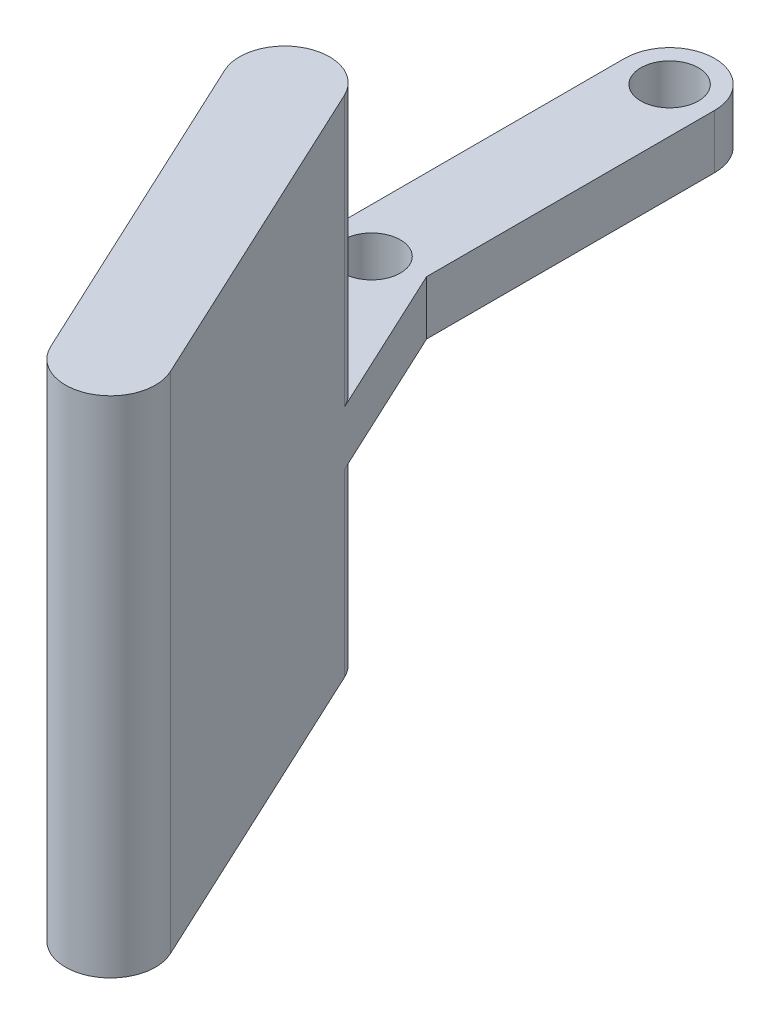
SolidWorks part; units mm, degrees
ref_plane "Front Plane" through (0, 0, 0) normal (0, 0, 1) x (1, 0, 0)
ref_plane "Top Plane" through (0, 0, 0) normal (0, 1, 0) x (1, 0, 0)
ref_plane "Right Plane" through (0, 0, 0) normal (1, 0, 0) x (0, 0, -1)
sketch "Sketch1" plane through (0, 0, 0) normal (0, 1, 0) x (1, 0, 0)
  line L0 (0, 0) -> (0, -16.5529) construction
  line L1 (2.5, 0) -> (2.5, -16.5529)
  line L2 (-2.5, 0) -> (-2.5, -16.5529)
  arc A0 (2.5, 0) -> (-2.5, 0) centre (0, 0) ccw
  arc A1 (-2.5, -16.5529) -> (2.5, -16.5529) centre (0, -16.5529) ccw
  point P3 (0, -8.2765)
  dimension "D1" = 2.5
  dimension "D2" = 16.5529
extrude "Boss-Extrude1" add sketch "Sketch1" along normal blind 3
sketch "Sketch2" plane through (0, 3, 0) normal (0, 1, 0) x (1, 0, 0)
  line L0 (0, -16.5529) -> (12.6866, -43.7384) construction
  line L1 (2.2655, -15.4957) -> (14.952, -42.6812)
  line L2 (-2.2655, -17.6102) -> (10.4211, -44.7957)
  line L3 (0, 0) -> (7.7578, 0) construction
  arc A0 (2.2655, -15.4957) -> (-2.2655, -17.6102) centre (0, -16.5529) ccw
  arc A1 (10.4211, -44.7957) -> (14.952, -42.6812) centre (12.6866, -43.7384) ccw
  point P3 (6.3433, -30.1457)
  dimension "D1" = 2.5
  dimension "D2" = 30
  dimension "D3" = 64.983
extrude "Boss-Extrude2" add sketch "Sketch2" against normal blind 3
sketch "Sketch3" plane through (0, 3, 0) normal (0, 1, 0) x (1, 0, 0)
  circle A0 centre (0, 0) radius 1.6
  circle A1 centre (0, -16.5529) radius 1.6
  dimension "D1" = 3.2
  dimension "D2" = 3.2
extrude "Cut-Extrude1" cut sketch "Sketch3" against normal through all
sketch "Sketch5" plane through (0, 0, 0) normal (0, -1, 0) x (1, 0, 0)
  line L0 (12.6866, 43.7384) -> (4.2289, 25.6148) construction
  line L1 (14.952, 42.6812) -> (6.4943, 24.5576)
  line L2 (10.4211, 44.7957) -> (1.9634, 26.672)
  line L3 (0, 0) -> (9.3795, 0) construction
  arc A0 (14.952, 42.6812) -> (10.4211, 44.7957) centre (12.6866, 43.7384) ccw
  arc A1 (1.9634, 26.672) -> (6.4943, 24.5576) centre (4.2289, 25.6148) ccw
  point P3 (8.4577, 34.6766)
  dimension "D3" = 2.5
  dimension "D1" = 64.983
  dimension "D2" = 20
extrude "Boss-Extrude3" add sketch "Sketch5" along normal blind 10
sketch "Sketch6" plane through (0, 3, 0) normal (0, 1, 0) x (1, 0, 0)
  line L0 (12.6866, -43.7384) -> (4.2289, -25.6148) construction
  line L3 (10.4211, -44.7957) -> (1.9634, -26.672)
  line L4 (14.952, -42.6812) -> (6.4943, -24.5576)
  line L5 (-2.2655, -17.6102) -> (10.4211, -44.7957) construction
  arc A2 (10.4211, -44.7957) -> (14.952, -42.6812) centre (12.6866, -43.7384) ccw
  arc A3 (6.4943, -24.5576) -> (1.9634, -26.672) centre (4.2289, -25.6148) ccw
  point P2 (8.4577, -34.6766)
  dimension "D1" = 2.5
  dimension "D2" = 20
extrude "Boss-Extrude4" add sketch "Sketch6" along normal blind 15
